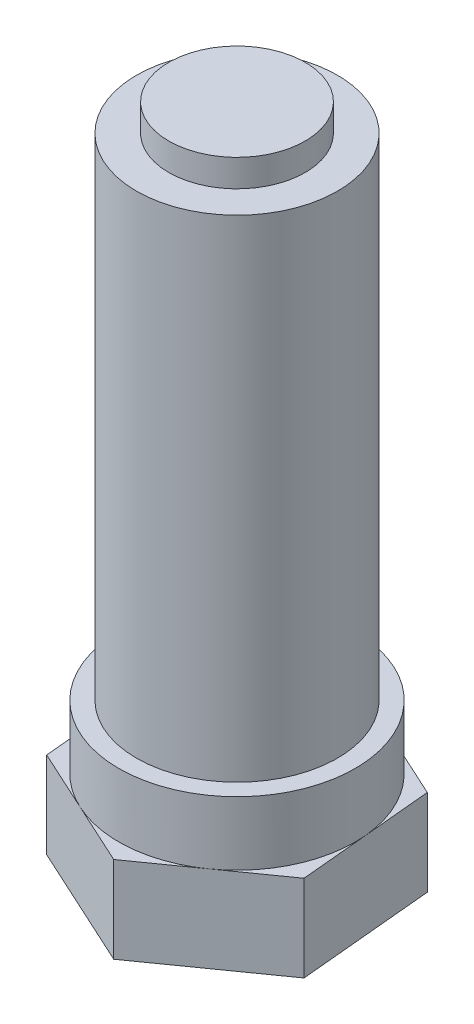
SolidWorks part; units mm, degrees
ref_plane "前视基准面" through (0, 0, 0) normal (0, 0, 1) x (1, 0, 0)
ref_plane "上视基准面" through (0, 0, 0) normal (0, 1, 0) x (1, 0, 0)
ref_plane "右视基准面" through (0, 0, 0) normal (1, 0, 0) x (0, 0, -1)
other "Configuration Table"
sketch "草图1" plane through (0, 0, 0) normal (0, 1, 0) x (1, 0, 0)
  line L1 (13.6394, -6.2689) -> (12.2487, 8.6777)
  line L2 (12.2487, 8.6777) -> (-1.3907, 14.9465)
  line L3 (-1.3907, 14.9465) -> (-13.6394, 6.2689)
  line L4 (-13.6394, 6.2689) -> (-12.2487, -8.6777)
  line L5 (-12.2487, -8.6777) -> (1.3907, -14.9465)
  line L6 (1.3907, -14.9465) -> (13.6394, -6.2689)
  circle A0 centre (0, 0) radius 13 construction
  dimension "D1" = 26
extrude "凸台-拉伸1" add sketch "草图1" along normal blind 9.5
sketch "草图2" plane through (0, 9.5, 0) normal (0, 1, 0) x (1, 0, 0)
  circle A0 centre (0, 0) radius 13
  dimension "D1" = 26
extrude "凸台-拉伸2" add sketch "草图2" along normal blind 7
sketch "草图3" plane through (0, 16.5, 0) normal (0, 1, 0) x (1, 0, 0)
  circle A0 centre (0, 0) radius 11.05
  dimension "D1" = 22.1
extrude "凸台-拉伸3" add sketch "草图3" along normal blind 54
sketch "草图4" plane through (0, 70.5, 0) normal (0, 1, 0) x (1, 0, 0)
  circle A0 centre (0, 0) radius 7.5
  dimension "D1" = 15
extrude "凸台-拉伸4" add sketch "草图4" along normal blind 3
